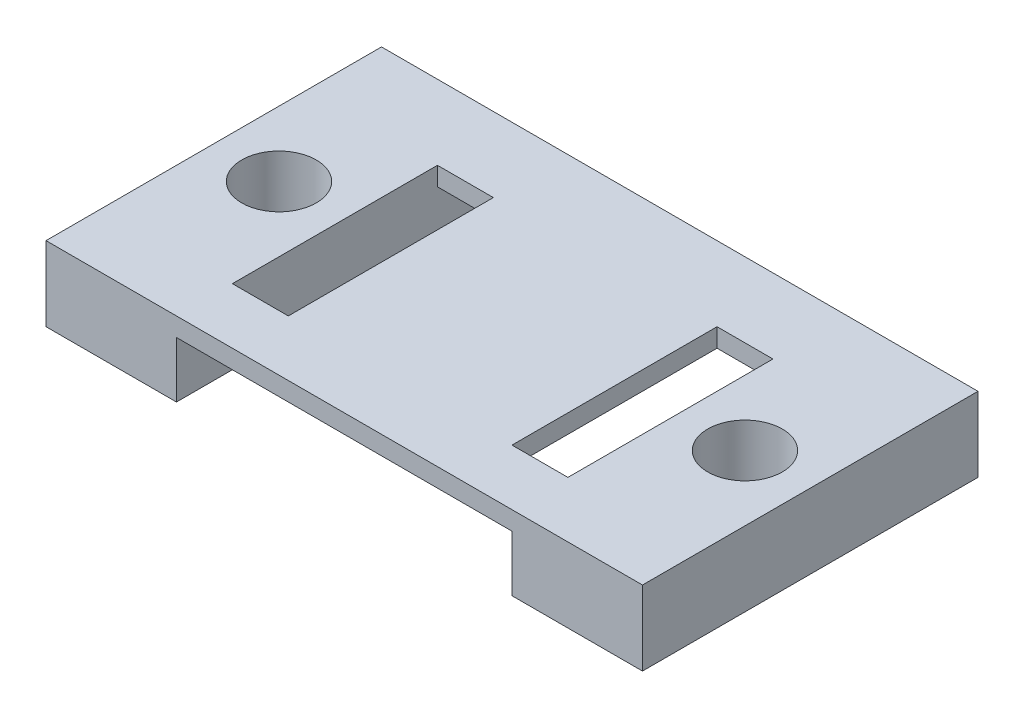
SolidWorks part; units mm, degrees
ref_plane "Front Plane" through (0, 0, 0) normal (0, 0, 1) x (1, 0, 0)
ref_plane "Top Plane" through (0, 0, 0) normal (0, 1, 0) x (1, 0, 0)
ref_plane "Right Plane" through (0, 0, 0) normal (1, 0, 0) x (0, 0, -1)
sketch "Sketch1" plane through (0, 0, 0) normal (0, 1, 0) x (1, 0, 0)
  line L0 (-9, 0) -> (9, 0)
  line L1 (9, 0) -> (9, 3)
  line L2 (9, 3) -> (6, 3)
  line L3 (6, 3) -> (6, 14)
  line L4 (6, 14) -> (9, 14)
  line L5 (9, 14) -> (9, 18)
  line L6 (9, 18) -> (-9, 18)
  line L7 (-9, 18) -> (-9, 14)
  line L8 (-9, 14) -> (-6, 14)
  line L9 (-6, 14) -> (-6, 3)
  line L10 (-6, 3) -> (-9, 3)
  line L11 (-9, 3) -> (-9, 0)
  point P3 (9, 16)
  dimension "D1" = 18
  dimension "D2" = 18
  dimension "D3" = 4
  dimension "D4" = 3
  dimension "D5" = 18
  dimension "D6" = 3
  dimension "D7" = 3
  dimension "D8" = 9
  dimension "D9" = 3
  dimension "D10" = 3
extrude "Boss-Extrude1" add sketch "Sketch1" along normal blind 1
sketch "Sketch2" plane through (0, 1, 0) normal (0, 1, 0) x (1, 0, 0)
  line L0 (-9, 18) -> (-9, 0)
  line L1 (-9, 0) -> (-16, 0)
  line L2 (-16, 0) -> (-16, 18)
  line L3 (-16, 18) -> (-9, 18)
  line L4 (0, 18) -> (0, 0) construction
  line L5 (9, 18) -> (-9, 18) construction
  line L6 (16, 18) -> (9, 18)
  line L7 (16, 0) -> (16, 18)
  line L8 (9, 0) -> (16, 0)
  line L9 (9, 18) -> (9, 0)
  circle A0 centre (-12.5, 9) radius 2
  circle A1 centre (12.5, 9) radius 2
  dimension "D2" = 4
  dimension "D1" = 7
  dimension "D3" = 9
  dimension "D4" = 3.5
extrude "Boss-Extrude2" add sketch "Sketch2" against normal blind 4
